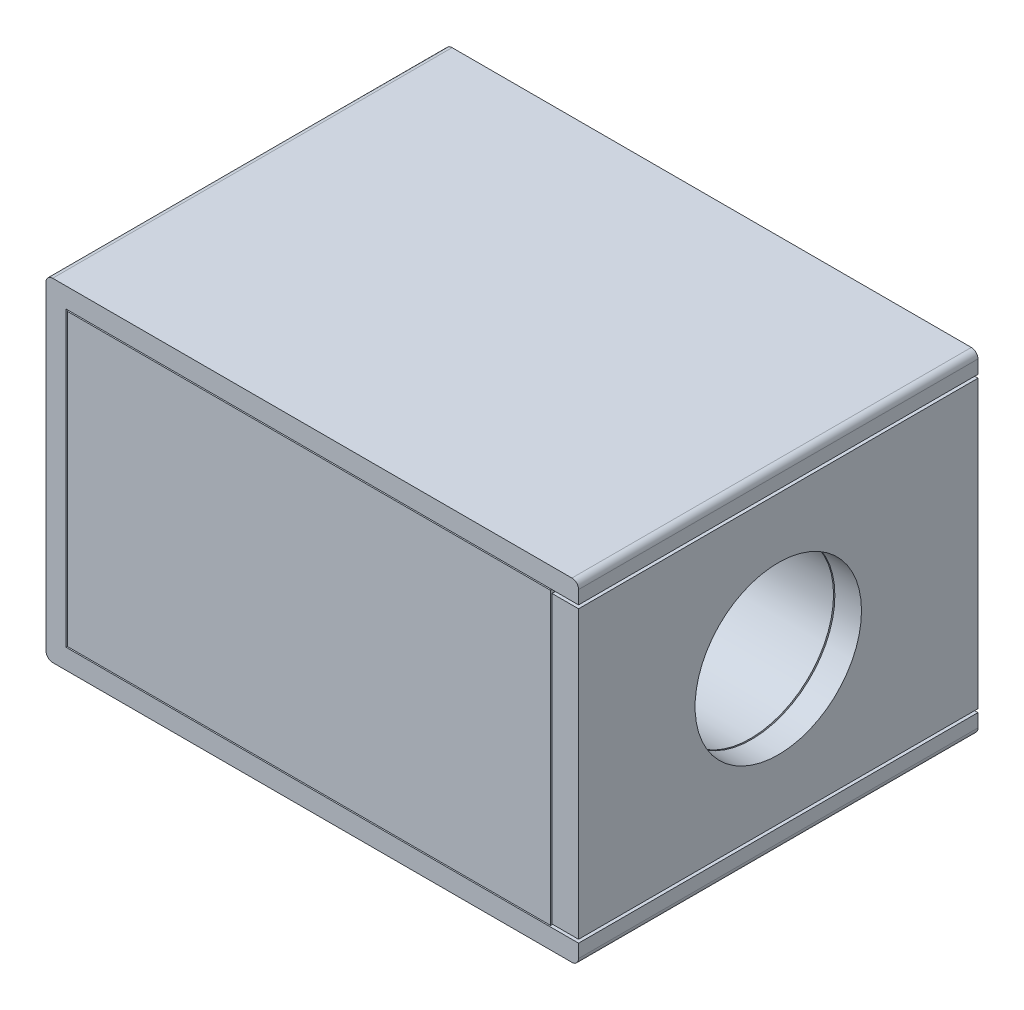
SolidWorks part; units mm, degrees
ref_plane "Front Plane" through (0, 0, 0) normal (0, 0, 1) x (1, 0, 0)
ref_plane "Top Plane" through (0, 0, 0) normal (0, 1, 0) x (1, 0, 0)
ref_plane "Right Plane" through (0, 0, 0) normal (1, 0, 0) x (0, 0, -1)
sketch "Sketch1" plane through (0, 0, 0) normal (0, 0, 1) x (1, 0, 0)
  line L0 (0, -24) -> (0, 24)
  line L1 (1, 25) -> (79, 25)
  line L2 (80, 24) -> (80, 22)
  line L3 (80, 22) -> (3, 22)
  line L4 (3, 22) -> (3, -22)
  line L5 (3, -22) -> (80, -22)
  line L6 (80, -22) -> (80, -24)
  line L7 (79, -25) -> (1, -25)
  arc A0 (80, -24) -> (79, -25) centre (79, -24) cw
  arc A1 (80, 24) -> (79, 25) centre (79, 24) ccw
  arc A2 (0, -24) -> (1, -25) centre (1, -24) ccw
  arc A3 (0, 24) -> (1, 25) centre (1, 24) cw
  point P4 (0, 0)
  dimension "D7" = 1
  dimension "D1" = 3
  dimension "D2" = 3
  dimension "D3" = 3
  dimension "D4" = 80
  dimension "D5" = 50
  dimension "D6" = 80
extrude "Boss-Extrude1" add sketch "Sketch1" along normal blind 60
sketch "Sketch2" plane through (80, 0, 0) normal (1, 0, 0) x (0, 0, -1)
  line L0 (-60, -22) -> (-60, 22) construction
  line L1 (-60, 21.5) -> (0, 21.5)
  line L2 (-60, 21.5) -> (-60, -21.5)
  line L3 (-60, -21.5) -> (0, -21.5)
  line L4 (0, 21.5) -> (0, -21.5)
  line L5 (0, -22) -> (0, 22) construction
  point P11 (-60, 0)
  dimension "D1" = 43
extrude "Boss-Extrude2" add sketch "Sketch2" against normal blind 4
sketch "Sketch3" plane through (0, 0, 60) normal (0, 0, 1) x (1, 0, 0)
  line L0 (3, 22) -> (80, 22) construction
  line L1 (3.2, 21.8) -> (75.8, 21.8)
  line L2 (3.2, 21.8) -> (3.2, -21.8)
  line L3 (3.2, -21.8) -> (75.8, -21.8)
  line L4 (75.8, 21.8) -> (75.8, -21.8)
  line L5 (3, -22) -> (3, 22) construction
  line L6 (76, 21.5) -> (76, -21.5) construction
  line L7 (80, -22) -> (3, -22) construction
  dimension "D1" = 0.2
  dimension "D2" = 0.2
  dimension "D3" = 0.2
  dimension "D4" = 0.2
extrude "Boss-Extrude3" add sketch "Sketch3" against normal up to surface (60 mm away) up to face at (40.5, 0, 0)
sketch "Sketch4" plane through (0, -25, 0) normal (0, -1, 0) x (1, 0, 0)
  line L0 (1, 48.5) -> (79, 48.5) construction
  line L1 (1, 60) -> (1, 0) construction
  line L2 (79, 60) -> (79, 0) construction
  line L3 (1, 11.5) -> (79, 11.5) construction
  line L4 (17, 60) -> (17, 0) construction
  line L5 (1, 60) -> (79, 60) construction
  line L6 (1, 0) -> (79, 0) construction
  line L7 (45, 60) -> (45, 0) construction
  line L8 (0, 60) -> (0, 0) construction
  line L9 (0, 30) -> (80, 30) construction
  line L10 (80, 60) -> (80, 0) construction
  circle A0 centre (17, 48.5) radius 2
  circle A1 centre (45, 48.5) radius 2
  circle A2 centre (45, 11.5) radius 2
  circle A3 centre (17, 11.5) radius 2
  dimension "D5" = 4
  dimension "D1" = 37
  dimension "D2" = 17
  dimension "D3" = 45
  dimension "D4" = 18.5
extrude "Cut-Extrude1" cut sketch "Sketch4" against normal blind 28
sketch "Sketch5" plane through (80, 0, 0) normal (1, 0, 0) x (0, 0, -1)
  line L0 (-30, 24) -> (-30, -24) construction
  line L1 (-60, 24) -> (0, 24) construction
  line L2 (-60, -24) -> (0, -24) construction
  line L3 (60, 0) -> (-60, 0) construction
  line L5 (-60, 21.5) -> (-60, -21.5) construction
  circle A0 centre (-30, 0) radius 12.5
  point P13 (0, 0)
  dimension "D1" = 25
extrude "Cut-Extrude2" cut sketch "Sketch5" against normal blind 60
sketch "Sketch6" plane through (0, 0, 0) normal (-1, 0, 0) x (0, 0, 1)
  line L0 (30, 24) -> (30, -24) construction
  line L1 (60, 24) -> (0, 24) construction
  line L2 (60, -24) -> (0, -24) construction
  line L3 (0, 0) -> (60, 0) construction
  line L4 (60, 24) -> (60, -24) construction
  circle A0 centre (30, 0) radius 5
  dimension "D1" = 10
extrude "Cut-Extrude3" cut sketch "Sketch6" against normal blind 42
